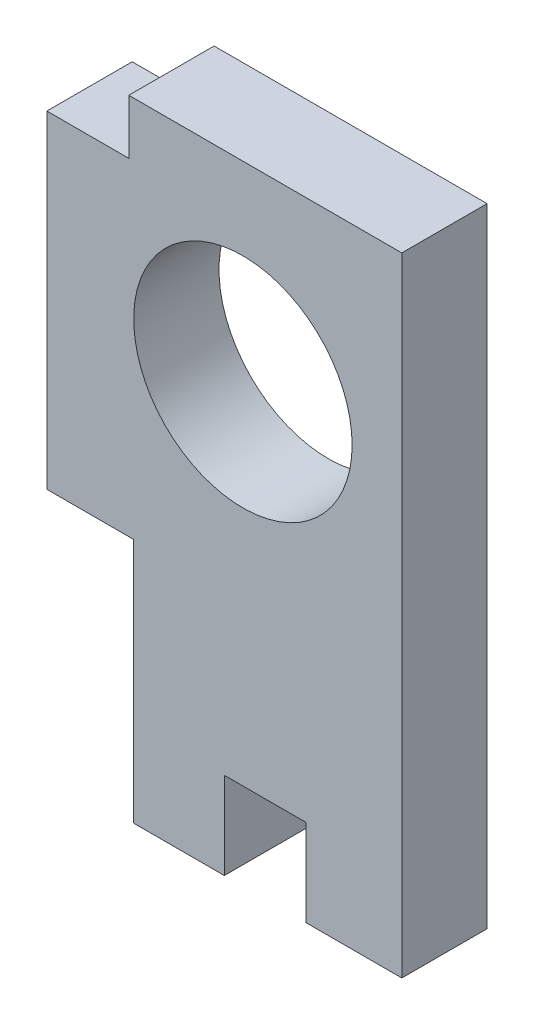
SolidWorks part; units mm, degrees
ref_plane "Front Plane" through (0, 0, 0) normal (0, 0, 1) x (1, 0, 0)
ref_plane "Top Plane" through (0, 0, 0) normal (0, 1, 0) x (1, 0, 0)
ref_plane "Right Plane" through (0, 0, 0) normal (1, 0, 0) x (0, 0, -1)
sketch "Sketch2" plane through (0, 0, 0) normal (0, 0, 1) x (1, 0, 0)
  line L16 (0, 9.5) -> (3, 9.5)
  line L17 (0, 11.5) -> (13, 11.5) construction
  line L18 (0, 11.5) -> (0, -11.5) construction
  line L19 (0, -11.5) -> (13, -11.5) construction
  line L20 (13, 11.5) -> (13, -11.5) construction
  line L21 (3, 9.5) -> (3, 11.5)
  line L22 (3, 11.5) -> (13, 11.5)
  line L23 (13, 11.5) -> (13, -11.5)
  line L24 (13, -11.5) -> (9.5, -11.5)
  line L25 (9.5, -11.5) -> (9.5, -8.32)
  line L26 (9.5, -8.32) -> (6.5, -8.32)
  line L27 (6.5, -8.32) -> (6.5, -11.5)
  line L28 (6.5, -11.5) -> (3.18, -11.5)
  line L29 (3.18, -11.5) -> (3.18, -2.5)
  line L30 (3.18, -2.5) -> (0, -2.5)
  line L31 (0, 9.5) -> (0, -2.5)
  circle A0 centre (7.18, 4.5) radius 4
  point P0 (13.2808, 24.6274)
  point P5 (0, 0)
  dimension "D9" = 8
  dimension "D1" = 23
  dimension "D2" = 3.5
  dimension "D3" = 10
  dimension "D4" = 3.18
  dimension "D5" = 3.18
  dimension "D6" = 3
  dimension "D7" = 9
  dimension "D8" = 12
  dimension "D10" = 7
  dimension "D11" = 7.18
extrude "Boss-Extrude1" add sketch "Sketch2" along normal blind 3.125
